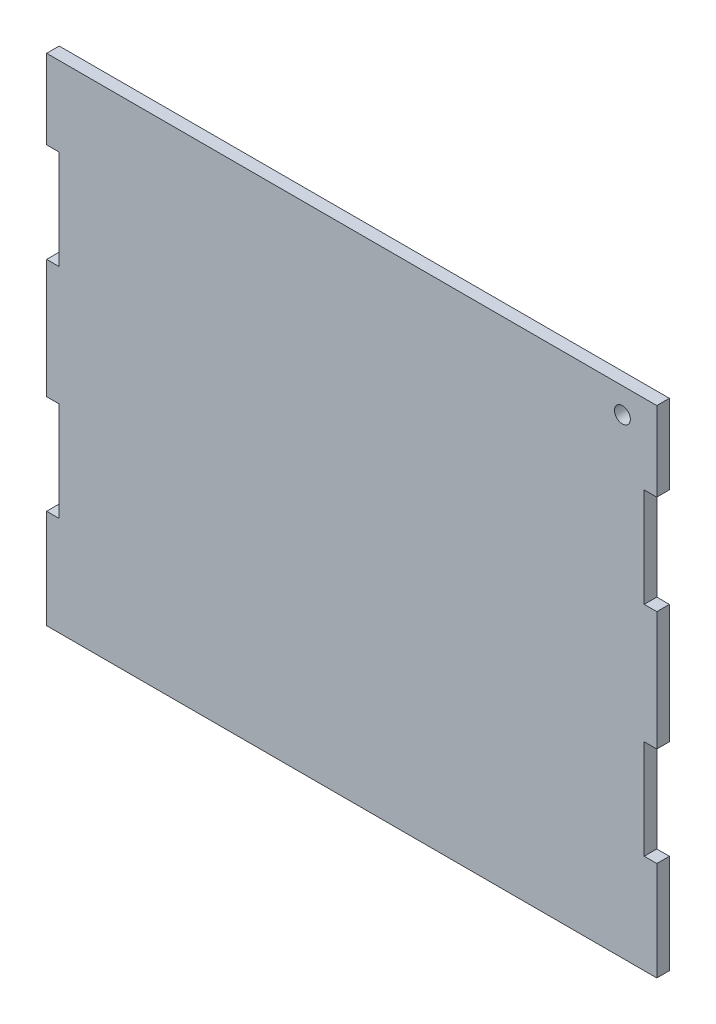
SolidWorks part; units mm, degrees
material "Beech"
ref_plane "Front Plane" through (0, 0, 0) normal (0, 0, 1) x (1, 0, 0)
ref_plane "Top Plane" through (0, 0, 0) normal (0, 1, 0) x (1, 0, 0)
ref_plane "Right Plane" through (0, 0, 0) normal (1, 0, 0) x (0, 0, -1)
sketch "Sketch1" plane through (0, 0, 0) normal (0, 0, 1) x (1, 0, 0)
  line L1 (0, 0) -> (307.7, 0)
  line L2 (0, 0) -> (0, 250)
  line L3 (0, 250) -> (307.7, 250)
  line L4 (307.7, 0) -> (307.7, 250)
  dimension "D1" = 250
  dimension "D2" = 307.7
extrude "Boss-Extrude1" add sketch "Sketch1" along normal blind 6.35
sketch "Sketch2" plane through (0, 0, 6.35) normal (0, 0, 1) x (1, 0, 0)
  line L0 (307.7, 0) -> (307.7, 250) construction
  line L1 (307.7, 50) -> (301.35, 50)
  line L2 (307.7, 50) -> (307.7, 100)
  line L3 (307.7, 100) -> (301.35, 100)
  line L4 (301.35, 50) -> (301.35, 100)
  line L5 (0, 0) -> (307.7, 0) construction
  line L6 (307.7, 160) -> (307.7, 210)
  line L7 (307.7, 160) -> (301.35, 160)
  line L8 (301.35, 160) -> (301.35, 210)
  line L9 (307.7, 210) -> (301.35, 210)
  line L10 (307.7, 250) -> (0, 250) construction
  line L11 (0, 250) -> (0, 0) construction
  line L12 (0, 50) -> (6.35, 50)
  line L13 (0, 50) -> (0, 100)
  line L14 (0, 100) -> (6.35, 100)
  line L15 (6.35, 50) -> (6.35, 100)
  line L16 (0, 160) -> (0, 210)
  line L17 (0, 160) -> (6.35, 160)
  line L18 (6.35, 160) -> (6.35, 210)
  line L19 (0, 210) -> (6.35, 210)
  line L20 (301.35, 250) -> (301.35, 0) construction
  circle A0 centre (290.35, 237.3) radius 4
  dimension "D11" = 8
  dimension "D1" = 6.35
  dimension "D2" = 50
  dimension "D3" = 50
  dimension "D5" = 40
  dimension "D6" = 6.35
  dimension "D7" = 50
  dimension "D8" = 50
  dimension "D10" = 40
  dimension "D12" = 11
  dimension "D13" = 12.7
  dimension "D4" = 2
  dimension "D9" = 2
extrude "Cut-Extrude1" cut sketch "Sketch2" against normal through all
